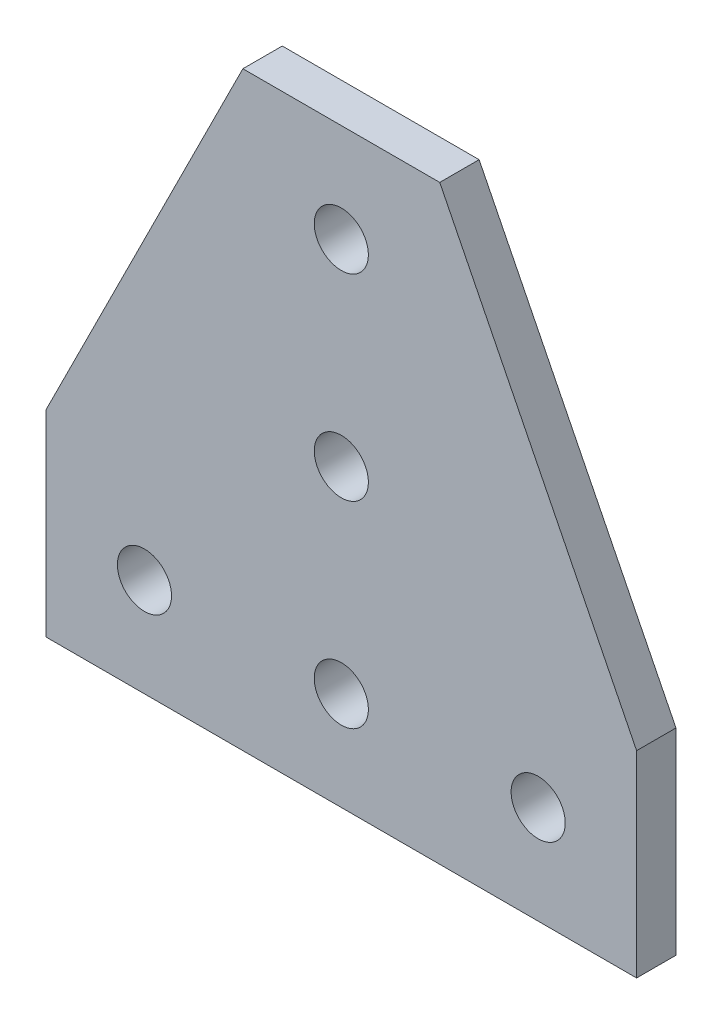
SolidWorks part; units mm, degrees
ref_plane "Front Plane" through (0, 0, 0) normal (0, 0, 1) x (1, 0, 0)
ref_plane "Top Plane" through (0, 0, 0) normal (0, 1, 0) x (1, 0, 0)
ref_plane "Right Plane" through (0, 0, 0) normal (1, 0, 0) x (0, 0, -1)
sketch "Sketch1" plane through (0, 0, 0) normal (0, 0, 1) x (1, 0, 0)
  line L0 (0, 0) -> (0, 20)
  line L1 (10, 10) -> (30, 10) construction
  line L2 (30, 10) -> (50, 10) construction
  line L3 (30, 10) -> (30, 30) construction
  line L4 (40, 60) -> (20, 60)
  line L5 (60, 0) -> (0, 0)
  line L6 (30, 30) -> (30, 50) construction
  line L7 (60, 20) -> (60, 0)
  line L8 (40, 60) -> (60, 20)
  line L9 (60, 10) -> (50, 10) construction
  line L10 (30, 60) -> (30, 50) construction
  line L11 (0, 20) -> (20, 60)
  circle A0 centre (10, 10) radius 2.75
  circle A1 centre (30, 10) radius 2.75
  circle A2 centre (50, 10) radius 2.75
  circle A3 centre (30, 30) radius 2.75
  circle A4 centre (30, 50) radius 2.75
  dimension "D1" = 20
  dimension "E" = 5.5
  dimension "D2" = 10
  dimension "C" = 60
  dimension "D3" = 20
  dimension "B" = 60
  dimension "D4" = 10
  dimension "D5" = 20
extrude "Boss-Extrude1" add sketch "Sketch1" along normal mid plane 4
